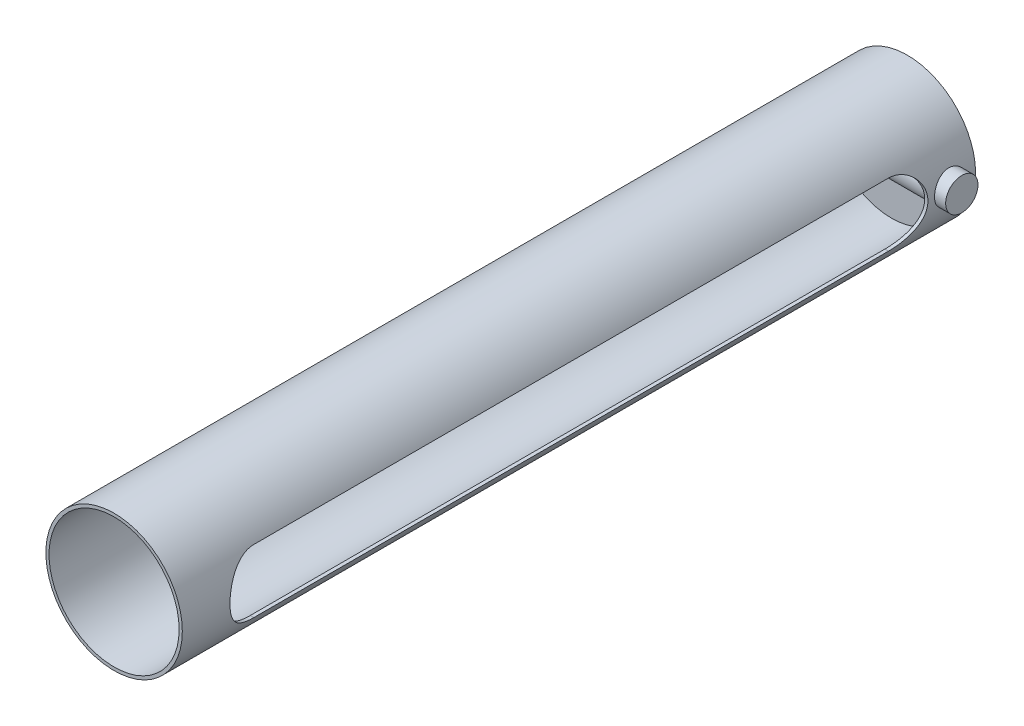
SolidWorks part; units mm, degrees
ref_plane "Front Plane" through (0, 0, 0) normal (0, 0, 1) x (1, 0, 0)
ref_plane "Top Plane" through (0, 0, 0) normal (0, 1, 0) x (1, 0, 0)
ref_plane "Right Plane" through (0, 0, 0) normal (1, 0, 0) x (0, 0, -1)
sketch "Sketch1" plane through (0, 0, 0) normal (0, 0, 1) x (1, 0, 0)
  circle A0 centre (0, 0) radius 10.922
  dimension "D1" = 21.844
extrude "Boss-Extrude1" add sketch "Sketch1" along normal blind 127
sketch "Sketch2" plane through (0, 0, 127) normal (0, 0, 1) x (1, 0, 0)
  circle A0 centre (0, 0) radius 10.414
  dimension "D1" = 20.828
extrude "Cut-Extrude1" cut sketch "Sketch2" against normal blind 124.46
sketch "Sketch4" plane through (0, 0, 0) normal (1, 0, 0) x (0, 0, -1)
  line L0 (-114.3, 0) -> (-12.7, 0) construction
  line L1 (-114.3, 5.0676) -> (-12.7, 5.0676)
  line L2 (-114.3, -5.0676) -> (-12.7, -5.0676)
  line L3 (0, 10.922) -> (-127, 10.922) construction
  arc A0 (-114.3, 5.0676) -> (-114.3, -5.0676) centre (-114.3, 0) ccw
  arc A1 (-12.7, -5.0676) -> (-12.7, 5.0676) centre (-12.7, 0) ccw
  point P2 (-63.5, 0)
  dimension "D1" = 10.1352
  dimension "D2" = 101.6
  dimension "D3" = 10.922
extrude "Cut-Extrude2" cut sketch "Sketch4" along normal blind 15.24
sketch "Sketch5" plane through (0, 0, 0) normal (1, 0, 0) x (0, 0, -1)
  circle A0 centre (-3.9846, 0) radius 2.5902
extrude "Boss-Extrude2" add sketch "Sketch5" along normal blind 12.7 contours A0
